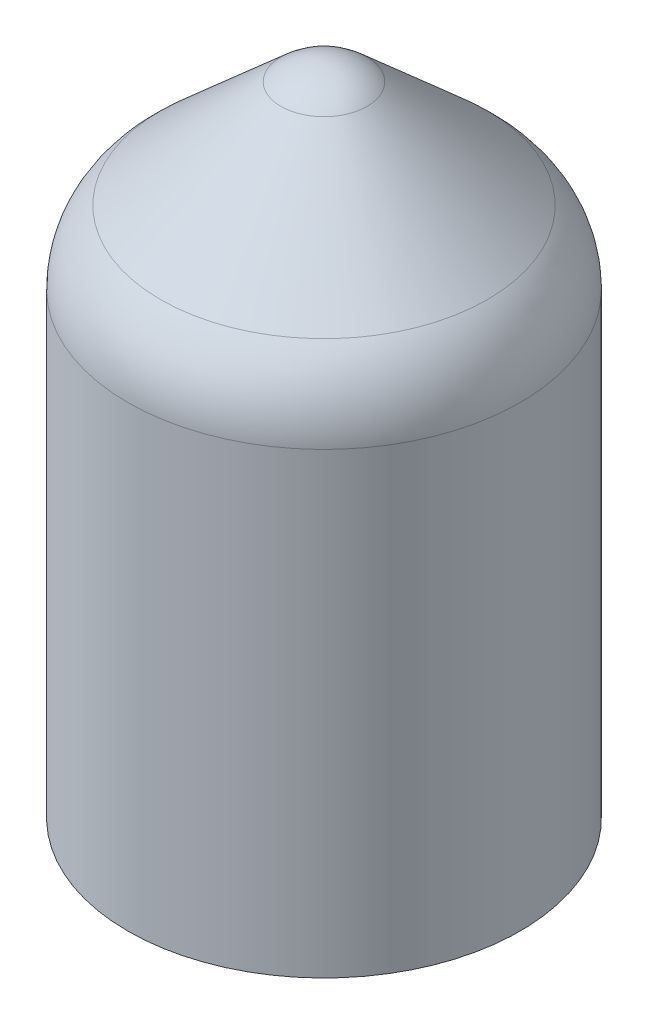
SolidWorks part; units mm, degrees
ref_plane "Front Plane" through (0, 0, 0) normal (0, 0, 1) x (1, 0, 0)
ref_plane "Top Plane" through (0, 0, 0) normal (0, 1, 0) x (1, 0, 0)
ref_plane "Right Plane" through (0, 0, 0) normal (1, 0, 0) x (0, 0, -1)
sketch "Sketch1" plane through (0, 0, 0) normal (0, 0, 1) x (1, 0, 0)
  line L1 (50, 162.2624) -> (13.155, 195)
  line L2 (0, 200) -> (0, 140)
  line L3 (60, 140) -> (60, 0)
  line L4 (60, 0) -> (0, 0)
  line L5 (0, 0) -> (0, 140)
  arc A0 (60, 140) -> (50, 162.2624) centre (30.2194, 140) ccw
  arc A1 (13.155, 195) -> (0, 200) centre (0, 180.1945) ccw
  point P2 (0, 0)
  point P4 (33.0329, 190)
  point P10 (42.2108, 179.3251)
  point P11 (27.4328, 191.6141)
  point P12 (0, 0)
  point P15 (2.7615, 171.1101)
  point P16 (0, 0)
  point P17 (0, 200)
  point P18 (0, 0)
  point P19 (16.6993, 200)
  point P20 (0, 0)
  point P21 (10.7881, 196.1253)
  point P22 (0, 0)
  point P23 (0, 0)
  point P24 (0, 0)
  dimension "D5" = 5
  dimension "D1" = 60
  dimension "D2" = 140
  dimension "D3" = 140
  dimension "D4" = 60
  dimension "D6" = 10
revolve "Revolve2" add sketch "Sketch1" angle 360 about L5
shell "Shell2" thickness 2
